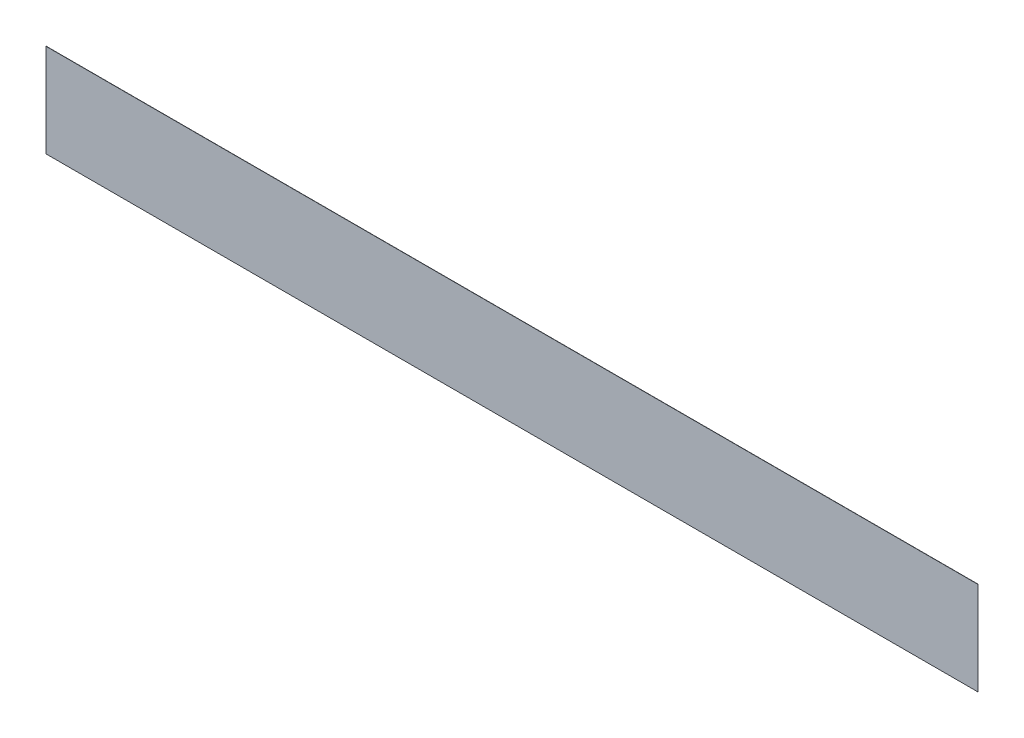
SolidWorks part; units mm, degrees
ref_plane "Front" through (0, 0, 0) normal (0, 0, 1) x (1, 0, 0)
ref_plane "Top" through (0, 0, 0) normal (0, 1, 0) x (1, 0, 0)
ref_plane "Right" through (0, 0, 0) normal (1, 0, 0) x (0, 0, -1)
sketch "Sketch1" plane through (0, 0, 0) normal (0, 0, 1) x (1, 0, 0)
  line L1 (-50, 1000) -> (19950, 1000)
  line L2 (-50, 1000) -> (-50, -1000)
  line L3 (-50, -1000) -> (19950, -1000)
  line L4 (19950, 1000) -> (19950, -1000)
  point P0 (0, 0)
  point P6 (0, 0)
  dimension "D1" = 20000
  dimension "D2" = 2000
  dimension "D3" = 50
extrude "Boss-Extrude1" add sketch "Sketch1" along normal blind 5
